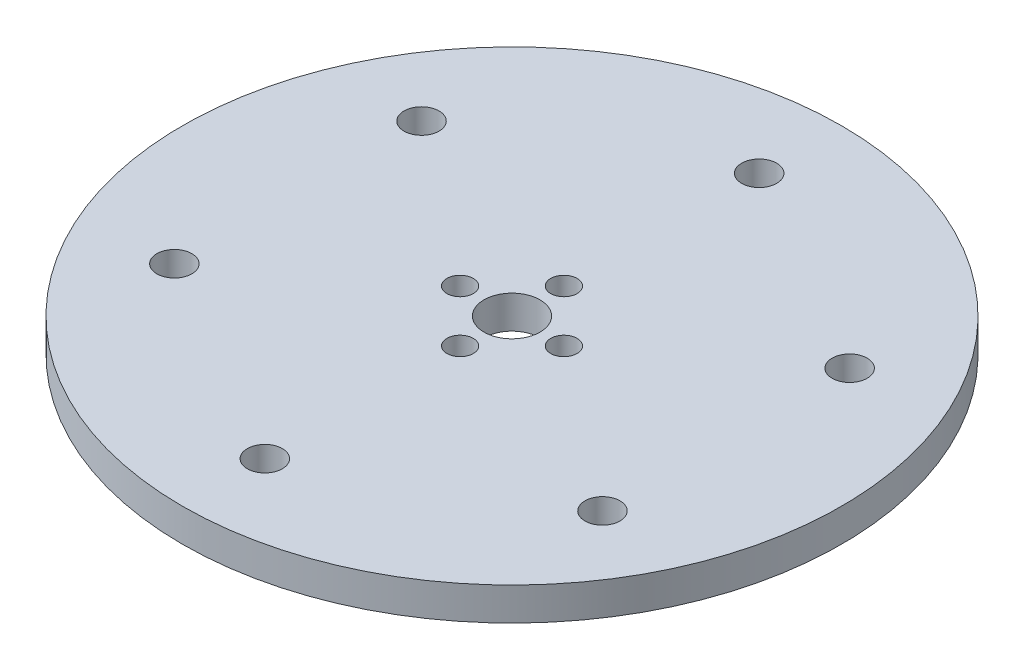
SolidWorks part; units mm, degrees
ref_plane "Front Plane" through (0, 0, 0) normal (0, 0, 1) x (1, 0, 0)
ref_plane "Top Plane" through (0, 0, 0) normal (0, 1, 0) x (1, 0, 0)
ref_plane "Right Plane" through (0, 0, 0) normal (1, 0, 0) x (0, 0, -1)
sketch "Sketch1" plane through (0, 0, 0) normal (0, 1, 0) x (1, 0, 0)
  circle A0 centre (0, 0) radius 50.8
  dimension "D1" = 101.6
extrude "Boss-Extrude1" add sketch "Sketch1" along normal blind 5.08
sketch "Sketch2" plane through (0, 5.08, 0) normal (0, 1, 0) x (1, 0, 0)
  circle A0 centre (0, -38.1) radius 2.6987
  circle A1 centre (-32.9956, -19.05) radius 2.6988
  circle A2 centre (-32.9956, 19.05) radius 2.6988
  circle A3 centre (0, 38.1) radius 2.6987
  circle A4 centre (32.9956, 19.05) radius 2.6987
  circle A5 centre (32.9956, -19.05) radius 2.6987
  point P15 (0, 0)
  dimension "D1" = 5.3975
  dimension "D2" = 38.1
  dimension "D3" = 6
extrude "Cut-Extrude1" cut sketch "Sketch2" against normal blind 5.08
sketch "Sketch3" plane through (0, 0, 0) normal (0, -1, 0) x (1, 0, 0)
  circle A0 centre (0, 0) radius 4.318
  circle A1 centre (0, -8.001) radius 2.032
  circle A2 centre (-8.001, 0) radius 2.032
  circle A3 centre (0, 8.001) radius 2.032
  circle A4 centre (8.001, 0) radius 2.032
  point P14 (0, 0)
  dimension "D1" = 8.001
  dimension "D2" = 4
extrude "Cut-Extrude2" cut sketch "Sketch3" against normal blind 5.08
